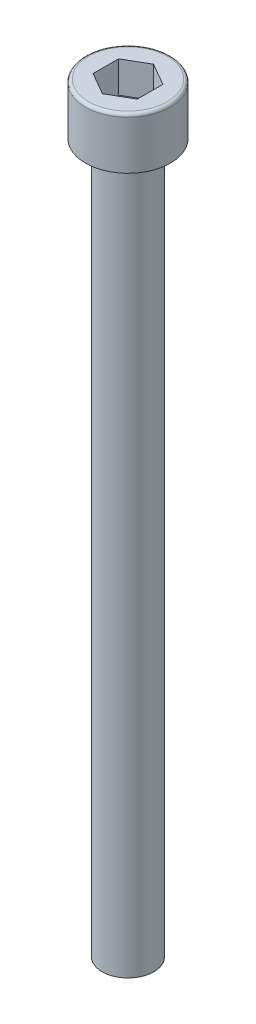
SolidWorks part; units mm, degrees
ref_plane "Front Plane" through (0, 0, 0) normal (0, 0, 1) x (1, 0, 0)
ref_plane "Top Plane" through (0, 0, 0) normal (0, 1, 0) x (1, 0, 0)
ref_plane "Right Plane" through (0, 0, 0) normal (1, 0, 0) x (0, 0, -1)
sketch "Sketch1" plane through (0, 0, 0) normal (0, 1, 0) x (1, 0, 0)
  circle A0 centre (0, 0) radius 2.0828
  dimension "D1" = 4.1656
extrude "Shaft" add sketch "Sketch1" against normal blind 57.15
sketch "Sketch2" plane through (0, 0, 0) normal (0, 1, 0) x (1, 0, 0)
  circle A0 centre (0, 0) radius 3.429
  dimension "D1" = 6.858
extrude "Head" add sketch "Sketch2" along normal blind 4.1656
fillet "Fillet1" radius 0.254 1 edges at (0, 4.1656, 3.429)
sketch "Sketch3" plane through (0, 4.1656, 0) normal (0, 1, 0) x (1, 0, 0)
  line L1 (0, 2.0622) -> (-1.7859, 1.0311)
  line L2 (-1.7859, 1.0311) -> (-1.7859, -1.0311)
  line L3 (-1.7859, -1.0311) -> (0, -2.0622)
  line L4 (0, -2.0622) -> (1.7859, -1.0311)
  line L5 (1.7859, -1.0311) -> (1.7859, 1.0311)
  line L6 (1.7859, 1.0311) -> (0, 2.0622)
  circle A0 centre (0, 0) radius 1.7859 construction
  dimension "D1" = 3.5719
extrude "Hex" cut sketch "Sketch3" against normal blind 2.54
